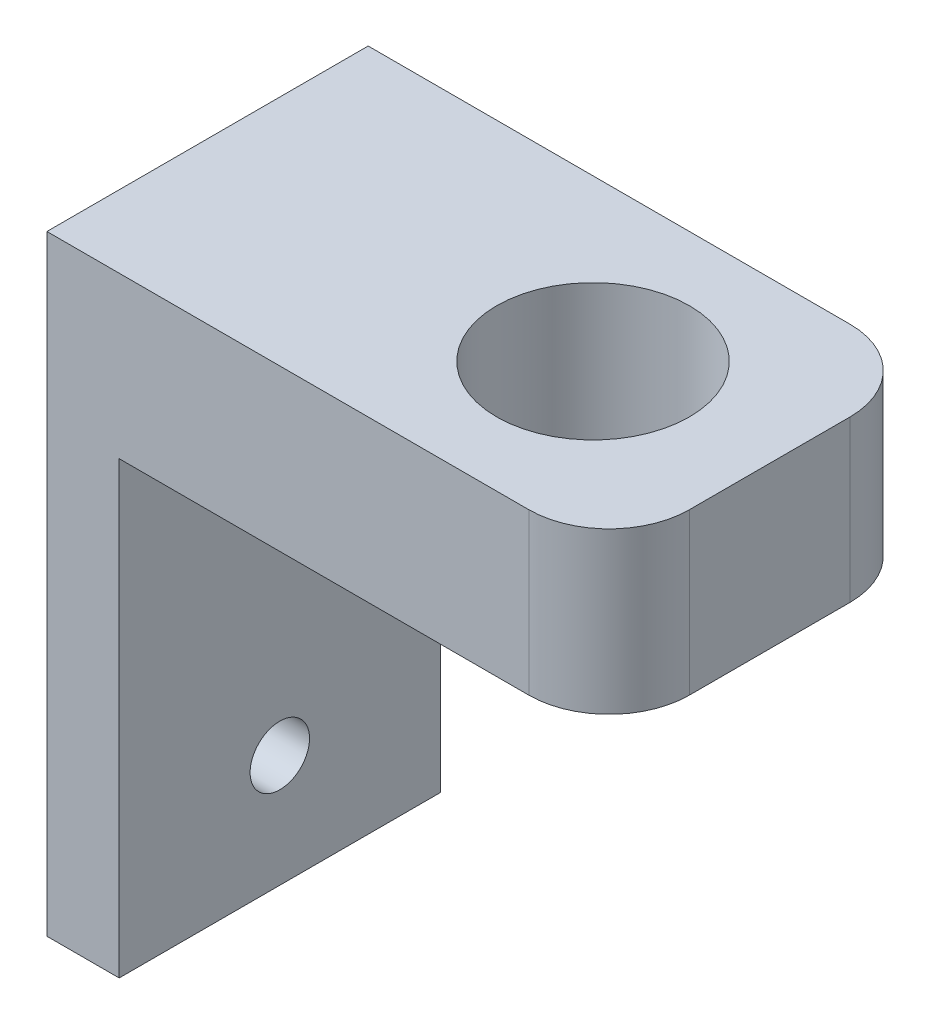
SolidWorks part; units mm, degrees
ref_plane "Front" through (0, 0, 0) normal (0, 0, 1) x (1, 0, 0)
ref_plane "Top" through (0, 0, 0) normal (0, 1, 0) x (1, 0, 0)
ref_plane "Right" through (0, 0, 0) normal (1, 0, 0) x (0, 0, -1)
sketch "Sketch1" plane through (0, 0, 0) normal (0, 1, 0) x (1, 0, 0)
  line L1 (-17.5, -10) -> (17.5, -10)
  line L2 (-17.5, -10) -> (-17.5, 10)
  line L3 (-17.5, 10) -> (17.5, 10)
  line L4 (17.5, -10) -> (17.5, 10)
  line L5 (-17.5, -10) -> (17.5, 10) construction
  line L6 (-17.5, 10) -> (17.5, -10) construction
  point P0 (0, 0)
  dimension "D2" = 20
  dimension "D3" = 35
extrude "Boss-Extrude1" add sketch "Sketch1" along normal blind 10
fillet "Fillet1" radius 5 2 edges at (17.5, 5, -10) (17.5, 5, 10)
sketch "Sketch4" plane through (0, 10, 0) normal (0, 1, 0) x (1, 0, 0)
  line L0 (17.5, -5) -> (17.5, 5) construction
  line L1 (-17.5, 0) -> (17.5, 0) construction
  line L2 (-17.5, 10) -> (-17.5, -10) construction
  circle A0 centre (6.5, 0) radius 6
  dimension "D1" = 12
  dimension "D2" = 24
extrude "Cut-Extrude2" cut sketch "Sketch4" against normal through all
sketch "Sketch5" plane through (0, 0, 0) normal (0, -1, 0) x (1, 0, 0)
  line L0 (12.5, -10) -> (-17.5, -10) construction
  line L1 (-17.5, 10) -> (-13, 10)
  line L2 (-17.5, 10) -> (-17.5, -10)
  line L3 (-17.5, -10) -> (-13, -10)
  line L4 (-13, 10) -> (-13, -10)
  dimension "D1" = 4.5
extrude "Boss-Extrude3" add sketch "Sketch5" along normal blind 28
sketch "Sketch6" plane through (-13, 0, 0) normal (1, 0, 0) x (0, 0, -1)
  line L0 (10, 0) -> (-10, 0) construction
  line L1 (0, -28) -> (0, 0) construction
  line L2 (10, -28) -> (-10, -28) construction
  circle A0 centre (0, -6) radius 1.85
  circle A1 centre (0, -6) radius 3.5 construction
  circle A2 centre (0, -21) radius 1.85
  circle A3 centre (0, -21) radius 3.5 construction
  dimension "D1" = 3.7
  dimension "D3" = 7
  dimension "D4" = 3.7
  dimension "D5" = 15
  dimension "D6" = 7
  dimension "D2" = 6
extrude "Cut-Extrude3" cut sketch "Sketch6" against normal through all
